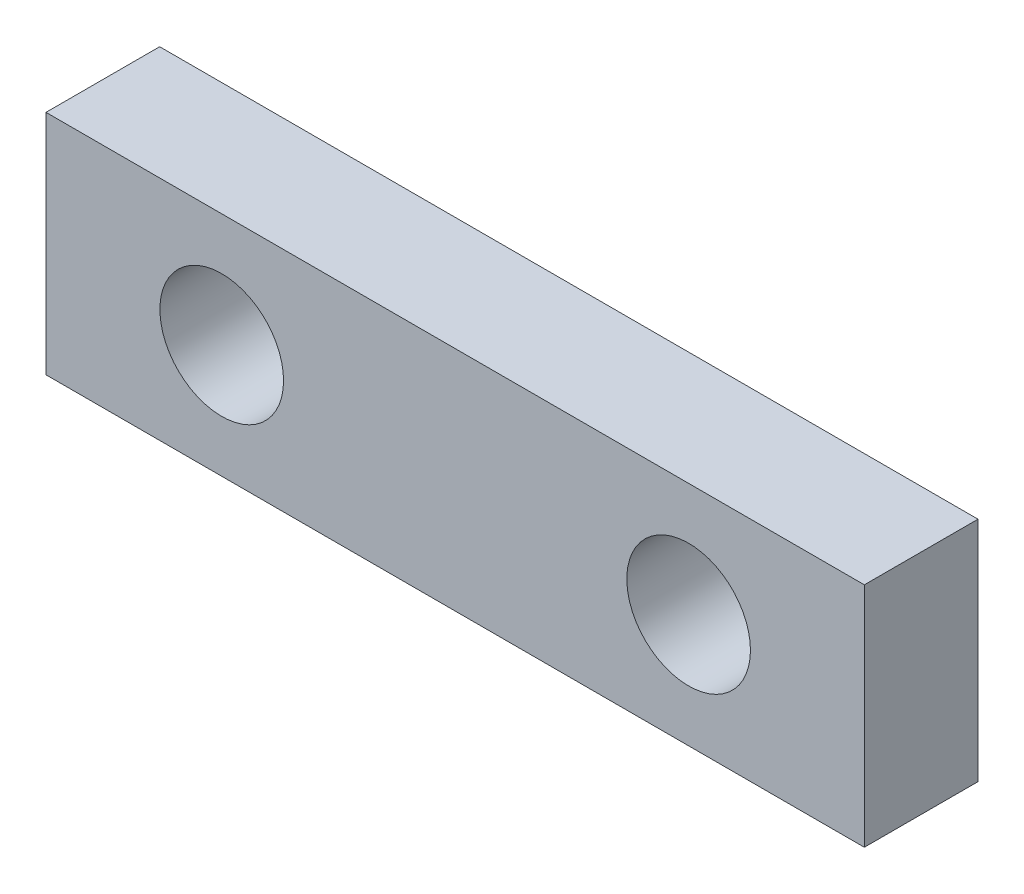
SolidWorks part; units mm, degrees
ref_plane "Front Plane" through (0, 0, 0) normal (0, 0, 1) x (1, 0, 0)
ref_plane "Top Plane" through (0, 0, 0) normal (0, 1, 0) x (1, 0, 0)
ref_plane "Right Plane" through (0, 0, 0) normal (1, 0, 0) x (0, 0, -1)
sketch "Sketch1" plane through (0, 0, 0) normal (0, 0, 1) x (1, 0, 0)
  line L1 (-11.43, -3.175) -> (11.43, -3.175)
  line L2 (-11.43, -3.175) -> (-11.43, 3.175)
  line L3 (-11.43, 3.175) -> (11.43, 3.175)
  line L4 (11.43, -3.175) -> (11.43, 3.175)
  line L5 (-11.43, -3.175) -> (11.43, 3.175) construction
  line L6 (-11.43, 3.175) -> (11.43, -3.175) construction
  point P0 (0, 0)
  dimension "D1" = 22.86
  dimension "D2" = 6.35
extrude "Boss-Extrude1" add sketch "Sketch1" along normal blind 3.175
sketch "Sketch2" plane through (0, 0, 3.175) normal (0, 0, 1) x (1, 0, 0)
  line L0 (11.43, 0) -> (6.5215, 0) construction
  line L1 (11.43, -3.175) -> (11.43, 3.175) construction
  line L2 (6.5215, 0) -> (-6.5214, 0) construction
  line L3 (-6.5214, 0) -> (-11.43, 0) construction
  line L4 (-11.43, 3.175) -> (-11.43, -3.175) construction
  dimension "D1" = 13.0429
hole_wizard "#4 Clearance Hole1" positions "Sketch4" profile "Sketch5" hole size "#4" standard "Ansi Inch" end condition through all
sketch "Sketch4" plane through (0, 0, 3.175) normal (0, 0, 1) x (1, 0, 0)
  point P1 (-6.5214, 0)
  point P4 (6.5215, 0)
sketch "Sketch5" plane through (-6.5214, 0, 3.175) normal (1, 0, 0) x (0, -1, 0)
  line L0 (0, 0) -> (0, 3.175)
  line L1 (0, 3.175) -> (1.7272, 3.175)
  line L2 (1.7272, 3.175) -> (1.7272, 0)
  line L5 (1.7272, 0) -> (0, 0)
  line L11 (0, -6.35) -> (0, 107.95) construction
  dimension "Thru Hole Dia." = 3.4544
  dimension "Thru Hole Depth" = 3.175
